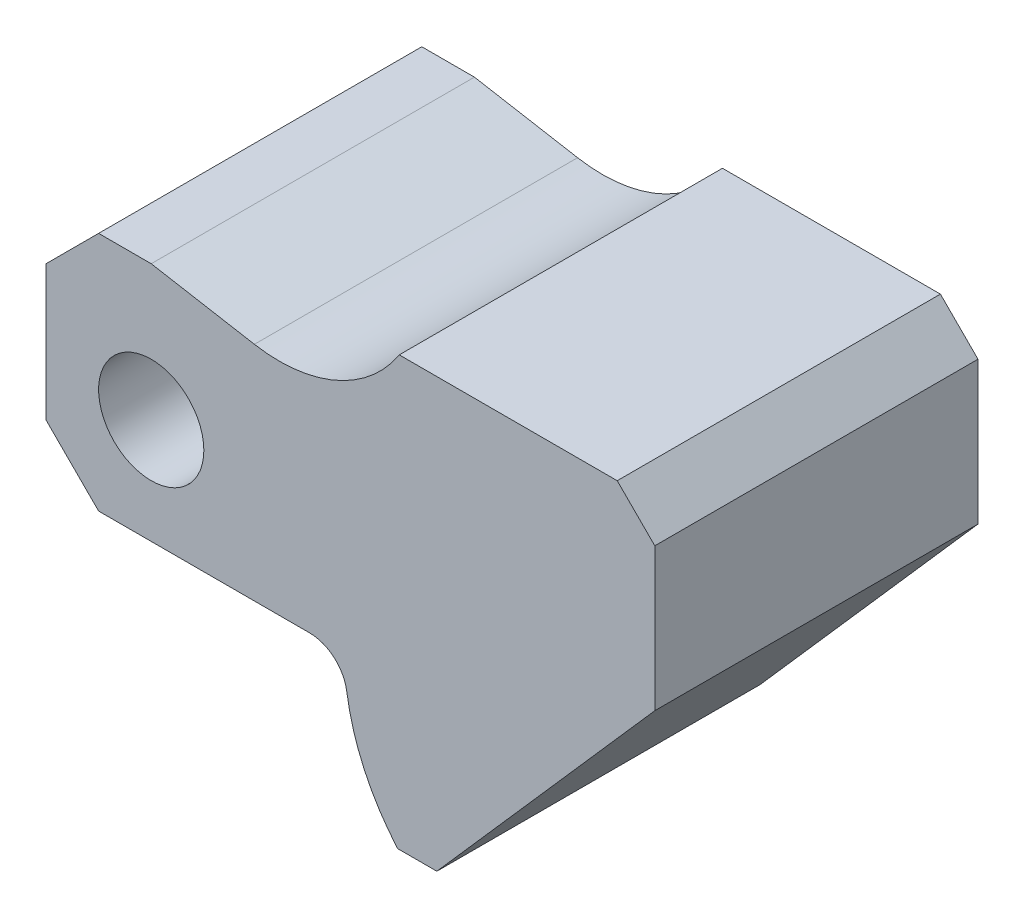
SolidWorks part; units mm, degrees
material "AISI 1020"
ref_plane "Front Plane" through (0, 0, 0) normal (0, 0, 1) x (1, 0, 0)
ref_plane "Top Plane" through (0, 0, 0) normal (0, 1, 0) x (1, 0, 0)
ref_plane "Right Plane" through (0, 0, 0) normal (1, 0, 0) x (0, 0, -1)
sketch "Sketch1" plane through (0, 0, 0) normal (0, 0, 1) x (1, 0, 0)
  line L0 (-355.6, 279.4) -> (-355.6, -177.8)
  line L1 (0, 0) -> (0, -355.6) construction
  line L2 (0, -355.6) -> (-177.8, -355.6)
  line L3 (0, -355.6) -> (0, -838.2) construction
  line L4 (-355.6, -177.8) -> (-177.8, -355.6)
  line L5 (0, -838.2) -> (965.2, -838.2) construction
  line L6 (0, 457.2) -> (-177.8, 457.2)
  line L7 (-355.6, 279.4) -> (-177.8, 457.2)
  line L8 (832.8169, -838.2) -> (965.2, -838.2)
  line L9 (965.2, -838.2) -> (1701.8, 0)
  line L10 (1701.8, 0) -> (1701.8, 482.6)
  line L11 (1701.8, 482.6) -> (1574.8, 609.6)
  line L12 (1574.8, 609.6) -> (838.2, 609.6)
  line L13 (0, -355.6) -> (3052.0209, -355.6) construction
  line L14 (0, 457.2) -> (348.7096, 395.7131)
  line L15 (0, -355.6) -> (535.0923, -355.6)
  circle A0 centre (0, 0) radius 177.8
  arc A1 (832.8169, -838.2) -> (660.7115, -463.9235) centre (1389.303, -355.6) cw
  arc A2 (660.7115, -463.9235) -> (535.0923, -355.6) centre (535.0923, -482.6) ccw
  arc A3 (348.7096, 395.7131) -> (838.2, 609.6) centre (432.5122, 870.9813) ccw
  point P5 (-355.6, 50.8)
  point P28 (899.0085, -838.2)
  dimension "D1" = 355.6
  dimension "D16" = 482.6
  dimension "D17" = 736.6
  dimension "D18" = 127
  dimension "D20" = 482.6
  dimension "D2" = 355.6
  dimension "D3" = 45
  dimension "D4" = 177.8
  dimension "D5" = 355.6
  dimension "D6" = 177.8
  dimension "D7" = 45
  dimension "D8" = 355.6
  dimension "D9" = 812.8
  dimension "D10" = 457.2
  dimension "D11" = 736.6
  dimension "D12" = 736.6
  dimension "D13" = 127
  dimension "D14" = 45
  dimension "D15" = 609.6
  dimension "D19" = 10
  dimension "D21" = 2057.4
  dimension "D22" = 1447.8
extrude "Boss-Extrude2" add sketch "Sketch1" along normal blind 1092.2
